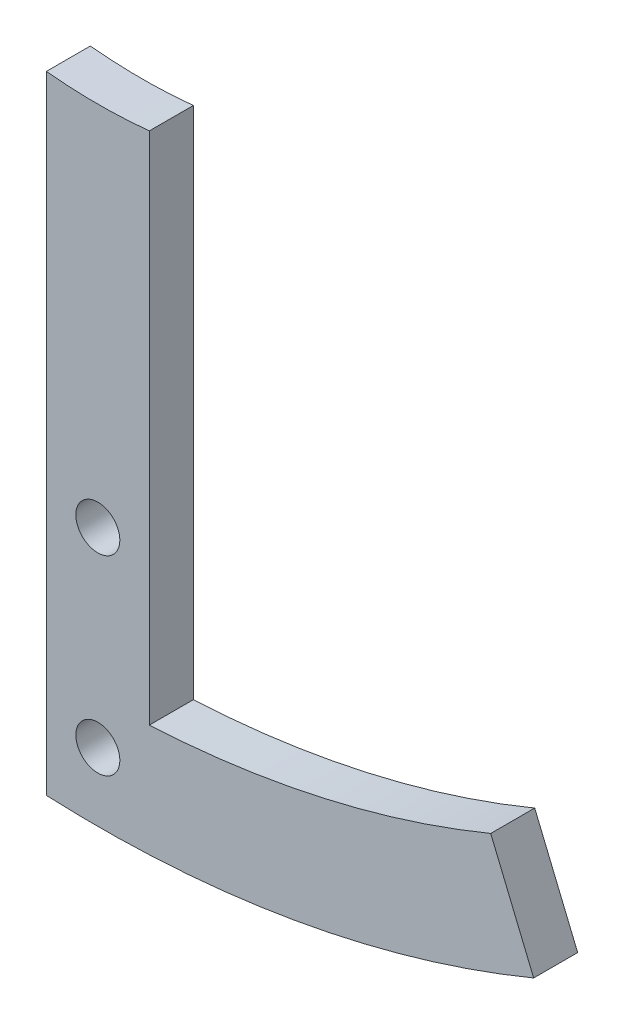
SolidWorks part; units mm, degrees
ref_plane "Front" through (0, 0, 0) normal (0, 0, 1) x (1, 0, 0)
ref_plane "Top" through (0, 0, 0) normal (0, 1, 0) x (1, 0, 0)
ref_plane "Right" through (0, 0, 0) normal (1, 0, 0) x (0, 0, -1)
ref_axis "Axis1" through (0, 0, -80.9) along (0, 0, 1)
sketch "草图1" plane through (0, 0, 0) normal (0, 0, 1) x (1, 0, 0)
  circle A0 centre (0, 0) radius 18
extrude "LaShenA" add sketch "草图1" along normal blind 3
sketch "SketchA" plane through (0, 0, 3) normal (0, 0, 1) x (1, 0, 0)
  line L0 (0, 0) -> (0, 18) construction
  arc A0 (0.4232, 13.4934) -> (-0.4232, 13.4934) centre (0, 0) ccw
  arc A1 (3.858, 18.7275) -> (-3.858, 18.7275) centre (0, 0) ccw
  arc A2 (-0.4232, 13.4934) -> (-1.2044, 14.1898) centre (-0.447, 14.253) cw
  arc A3 (1.2044, 14.1898) -> (0.4232, 13.4934) centre (0.447, 14.253) cw
  circle A4 centre (0, 0) radius 15.0351 construction
  circle A5 centre (0, 0) radius 18 construction
  circle A6 centre (0, 0) radius 13.5 construction
  circle A7 centre (0, 0) radius 16 construction
  spline S0 degree 3 poles (1.2044, 14.1898) (1.2266, 14.4552) (1.2138, 14.7739) (1.2737, 15.1106) (1.2991, 15.2114) (1.3214, 15.2911) (1.3499, 15.3823) (1.3851, 15.4846) (1.4278, 15.5978) (1.4786, 15.7214) (1.5382, 15.8552) (1.6071, 15.9987) (1.686, 16.1514) (1.7754, 16.3129) (1.876, 16.4827) (1.9884, 16.6603) (2.1129, 16.8451) (2.2502, 17.0365) (2.4007, 17.234) (2.5649, 17.4369) (2.7432, 17.6446) (2.9361, 17.8564) (3.1439, 18.0718) (3.4474, 18.3685) (3.6895, 18.585) (3.858, 18.7275) knots 0.122308 0.122308 0.122308 0.122308 0.250611 0.276296 0.287604 0.300968 0.316388 0.333864 0.353395 0.374983 0.398627 0.424327 0.452082 0.481894 0.513762 0.547685 0.583665 0.6217 0.661792 0.703939 0.748143 0.794402 0.842718 0.893089 1 1 1 1
  spline S1 degree 3 poles (-1.2044, 14.1898) (-1.2266, 14.4552) (-1.2138, 14.7739) (-1.2737, 15.1106) (-1.2991, 15.2114) (-1.3214, 15.2911) (-1.3499, 15.3823) (-1.3851, 15.4846) (-1.4278, 15.5978) (-1.4786, 15.7214) (-1.5382, 15.8552) (-1.6071, 15.9987) (-1.686, 16.1514) (-1.7754, 16.3129) (-1.876, 16.4827) (-1.9884, 16.6603) (-2.1129, 16.8451) (-2.2502, 17.0365) (-2.4007, 17.234) (-2.5649, 17.4369) (-2.7432, 17.6446) (-2.9361, 17.8564) (-3.1439, 18.0718) (-3.4474, 18.3685) (-3.6895, 18.585) (-3.858, 18.7275) knots 0.122308 0.122308 0.122308 0.122308 0.250611 0.276296 0.287604 0.300968 0.316388 0.333864 0.353395 0.374983 0.398627 0.424327 0.452082 0.481894 0.513762 0.547685 0.583665 0.6217 0.661792 0.703939 0.748143 0.794402 0.842718 0.893089 1 1 1 1
  dimension "D1" = 0.76
  dimension "Db" = 30.0702
  dimension "Da" = 36
  dimension "Df" = 27
  dimension "Dn" = 32
extrude "Cut-ExtrudeA" cut sketch "SketchA" against normal blind 3
pattern_circular "www.KYTool.cn" count 16 over 360 about axis through (0, 0, -80.9) along (0, 0, 1) of "Cut-ExtrudeA"
sketch "草图3" plane through (0, 0, 0) normal (0, 0, -1) x (-1, 0, 0)
  circle A0 centre (0, 0) radius 1.5
extrude "切除-拉伸2" cut sketch "草图3" against normal blind 10
sketch "草图4" plane through (0, 0, 0) normal (0, 0, -1) x (-1, 0, 0)
  line L0 (0, 0) -> (5, 0)
  circle A0 centre (5, 0) radius 1.5
  circle A1 centre (0, -5) radius 1.5
  circle A2 centre (-5, 0) radius 1.5
  circle A3 centre (0, 5) radius 1.5
  point P13 (0, 0)
  dimension "D1" = 4
extrude "切除-拉伸3" cut sketch "草图4" against normal blind 10
sketch "草图5" plane through (0, 0, 0) normal (0, 0, -1) x (-1, 0, 0)
  line L0 (-3.5116, -17.6541) -> (-3.5116, -77.6541)
  line L1 (3.5116, -17.6541) -> (3.5116, -77.6541)
  line L3 (0, 0) -> (-5.1662, -12.4724)
  line L4 (-5.1662, -12.4724) -> (-6.8883, -16.6298)
  line L5 (-6.8883, -16.6298) -> (-29.717, -71.7431)
  line L6 (-3.5116, -17.6541) -> (3.5116, -17.6541)
  line L7 (-3.5116, -17.6541) -> (-3.5116, -11.9836)
  line L8 (3.5116, -17.6541) -> (3.5116, -11.9836)
  line L9 (-3.5116, -11.9836) -> (3.5116, -11.9836)
  circle A1 centre (0, 0) radius 18
  arc A2 (2.8593, -17.7715) -> (4.1592, -17.5129) centre (0, 0) ccw construction
  arc A3 (-4.1592, -17.5129) -> (-2.8593, -17.7715) centre (0, 0) ccw construction
  arc A5 (-5.5547, -12.3043) -> (-4.7727, -12.6282) centre (0, 0) ccw construction
  circle A6 centre (0, 0) radius 77.6541
  circle A7 centre (0, 0) radius 70
extrude "凸台-拉伸3" add sketch "草图5" against normal blind 3 contours L9 L7 L6 L8 | L0 A7 L1 A1 | A7 L0 A6 L1 | A7 L5 A6 L0 | L6 A1
sketch "草图6" plane through (0, 0, 3) normal (0, 0, 1) x (1, 0, 0)
  circle A2 centre (0, -60) radius 1.5
  circle A3 centre (0, -73) radius 1.5
extrude "切除-拉伸4" cut sketch "草图6" against normal blind 3
sketch "草图8" plane through (0, 0, 3) normal (0, 0, 1) x (1, 0, 0)
  circle A0 centre (0, 0) radius 35
extrude "切除-拉伸5" cut sketch "草图8" against normal blind 3
